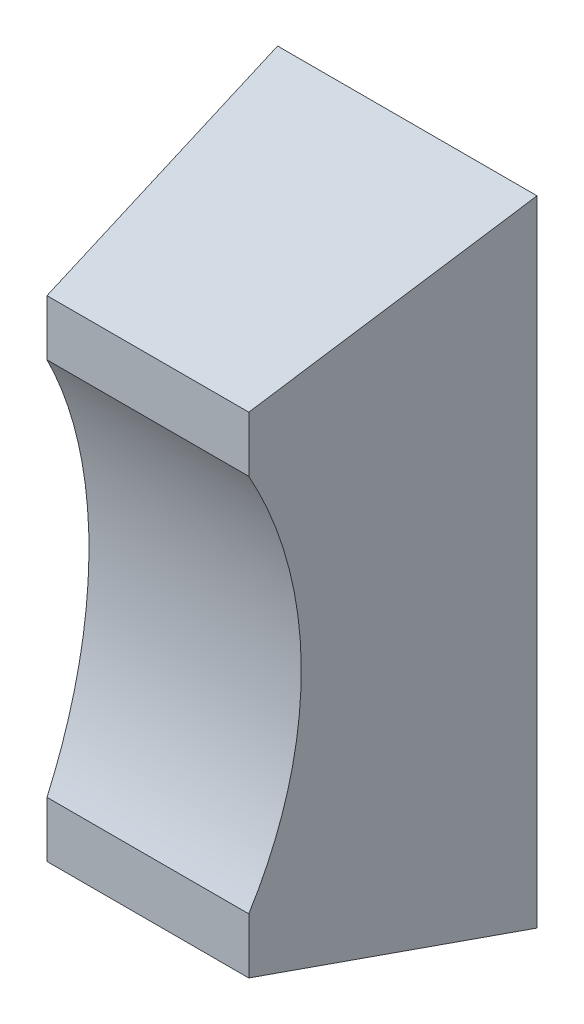
SolidWorks part; units mm, degrees
ref_plane "Front Plane" through (0, 0, 0) normal (0, 0, 1) x (1, 0, 0)
ref_plane "Top Plane" through (0, 0, 0) normal (0, 1, 0) x (1, 0, 0)
ref_plane "Right Plane" through (0, 0, 0) normal (1, 0, 0) x (0, 0, -1)
sketch "Sketch1" plane through (0, 0, 0) normal (0, 0, 1) x (1, 0, 0)
  line L1 (-4.5, 11) -> (4.5, 11)
  line L2 (-4.5, 11) -> (-4.5, -11)
  line L3 (-4.5, -11) -> (4.5, -11)
  line L4 (4.5, 11) -> (4.5, -11)
  line L5 (0, -11) -> (0, 11) construction
  line L6 (-4.5, 0) -> (4.5, 0) construction
  point P0 (0, 0)
  dimension "D1" = 9
  dimension "D2" = 22
ref_plane "Plane1" through (0, 0, 9) normal (0, 0, 1) x (1, 0, 0)
sketch "Sketch2" plane through (0, 0, 9) normal (0, 0, 1) x (1, 0, 0)
  line L0 (0, -11) -> (0, 11) construction
  line L1 (-3.5, 8.5) -> (3.5, 8.5)
  line L2 (-3.5, 8.5) -> (-3.5, -8.5)
  line L3 (-3.5, -8.5) -> (3.5, -8.5)
  line L4 (3.5, 8.5) -> (3.5, -8.5)
  line L5 (0, -8.5) -> (0, 8.5) construction
  line L6 (-3.5, 0) -> (3.5, 0) construction
  point P0 (0, 0)
  dimension "D1" = 7
  dimension "D2" = 17
loft "Loft1" add profiles "Sketch2", "Sketch1"
sketch "Sketch3" plane through (0, 0, 0) normal (0, 0, -1) x (-1, 0, 0)
  line L1 (-0.65, 2.2) -> (0.65, 2.2)
  line L2 (-0.65, 2.2) -> (-0.65, -2.2)
  line L3 (-0.65, -2.2) -> (0.65, -2.2)
  line L4 (0.65, 2.2) -> (0.65, -2.2)
  line L5 (0, -2.2) -> (0, 2.2) construction
  line L6 (-0.65, 0) -> (0.65, 0) construction
  point P0 (0, 0)
  dimension "D1" = 4.4
  dimension "D2" = 1.3
extrude "Cut-Extrude1" cut sketch "Sketch3" against normal blind 5
sketch "Sketch4" plane through (0, 0, 0) normal (1, 0, 0) x (0, 0, -1)
  line L0 (0, 0) -> (-21.3518, 0) construction
  line L1 (-9.8611, 7.9826) -> (-10.1406, -8.3706)
  arc A0 (-9.8611, 7.9826) -> (-10.1406, -8.3706) centre (-21.3518, 0) cw
extrude "Cut-Extrude2" cut sketch "Sketch4" against normal mid plane 20
